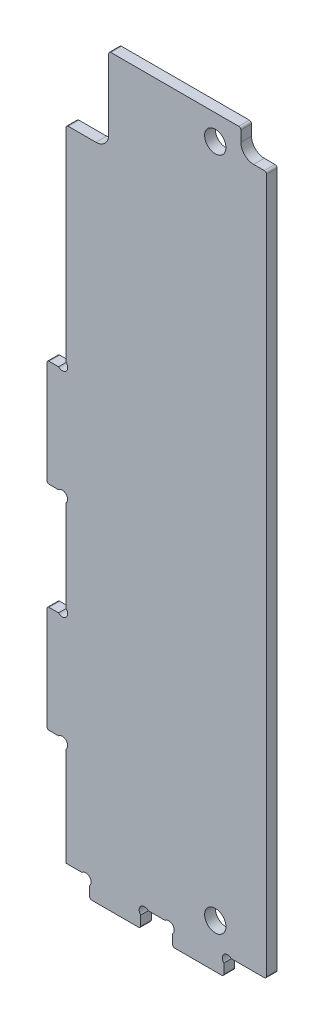
SolidWorks part; units mm, degrees
ref_plane "Ebene vorne" through (0, 0, 0) normal (0, 0, 1) x (1, 0, 0)
ref_plane "Ebene oben" through (0, 0, 0) normal (0, 1, 0) x (1, 0, 0)
ref_plane "Ebene rechts" through (0, 0, 0) normal (1, 0, 0) x (0, 0, -1)
sketch "Sketch1" plane through (0, 0, 0) normal (0, 0, 1) x (1, 0, 0)
  line L1 (0, 0) -> (5.5, 0)
  line L2 (0, 0) -> (0, 25)
  line L3 (10, 170) -> (47, 170)
  line L4 (47, 0) -> (47, 170)
  line L7 (0, 25) -> (-4.5, 25)
  line L8 (-4.5, 25) -> (-4.5, 50)
  line L9 (-4.5, 50) -> (0, 50)
  line L10 (0, 50) -> (0, 75)
  line L11 (0, 75) -> (-4.5, 75)
  line L12 (-4.5, 75) -> (-4.5, 100)
  line L13 (-4.5, 100) -> (0, 100)
  line L14 (0, 100) -> (0, 150)
  line L15 (37, 0) -> (37, -4.5)
  line L16 (0, 150) -> (10, 150)
  line L17 (10, 170) -> (10, 150)
  line L18 (37, -4.5) -> (25, -4.5)
  line L19 (25, -4.5) -> (25, 0)
  line L20 (47, 160) -> (47, -4.5) construction
  line L21 (17.5, 0) -> (17.5, -4.5)
  line L22 (17.5, -4.5) -> (5.5, -4.5)
  line L23 (5.5, -4.5) -> (5.5, 0)
  line L24 (37, 0) -> (47, 0)
  line L25 (17.5, 0) -> (25, 0)
  circle A0 centre (35, 5.85) radius 2.5
  circle A1 centre (35, 164.15) radius 2.5
  dimension "D3" = 5
  dimension "D2" = 170
  dimension "D4" = 12
  dimension "D5" = 5.85
  dimension "D6" = 25
  dimension "D7" = 4.5
  dimension "D8" = 25
  dimension "D9" = 47
  dimension "D10" = 5.85
  dimension "D11" = 12
  dimension "D12" = 4.5
  dimension "D13" = 10
  dimension "D14" = 10
  dimension "D15" = 7.5
  dimension "D16" = 12
  dimension "D17" = 20
extrude "Boss-Extrude1" add sketch "Sketch1" along normal blind 2.5
sketch "Sketch3" plane through (0, 0, 2.5) normal (0, 0, 1) x (1, 0, 0)
  line L0 (47, 170) -> (10, 170) construction
  line L2 (41, 170) -> (47, 170)
  line L3 (41, 170) -> (41, 164)
  line L4 (41, 164) -> (47, 164)
  line L5 (47, 170) -> (47, 164)
  line L6 (47, 0) -> (47, 170) construction
  dimension "D1" = 6
  dimension "D2" = 6
extrude "Cut-Extrude2" cut sketch "Sketch3" against normal through all
sketch "Sketch2" plane through (0, 0, 2.5) normal (0, 0, 1) x (1, 0, 0)
  line L0 (-0.8839, 24.1161) -> (-0.8839, 25) construction
  line L1 (0, 25) -> (0, 0) construction
  line L3 (-0.8839, 24.1161) -> (0, 24.1161) construction
  line L4 (-4.5, 25) -> (0, 25) construction
  line L8 (-4.5, 50) -> (-4.5, 25) construction
  line L9 (-4.5, 37.5) -> (-10.3856, 37.5) construction
  line L11 (0, 75) -> (0, 50) construction
  line L12 (0, 62.5) -> (-7.4428, 62.5) construction
  line L14 (-4.5, 100) -> (-4.5, 75) construction
  line L15 (-4.5, 87.5) -> (-15.0134, 87.5) construction
  line L31 (5.5, -0.8839) -> (4.6161, -0.8839) construction
  line L33 (5.5, 0) -> (5.5, -4.5) construction
  line L34 (4.6161, -0.8839) -> (4.6161, 0) construction
  line L36 (5.5, -4.5) -> (17.5, -4.5) construction
  line L37 (11.5, -4.5) -> (11.5, -1.3725) construction
  line L39 (17.5, 0) -> (25, 0) construction
  line L40 (21.25, 0) -> (21.25, -3.5992) construction
  line L41 (0, 0) -> (5.5, 0) construction
  line L42 (25, -4.5) -> (37, -4.5) construction
  line L43 (31, -4.5) -> (31, -0.6862) construction
  circle A0 centre (-0.8839, 24.1161) radius 1.25
  circle A1 centre (-0.8839, 50.8839) radius 1.25
  circle A2 centre (-0.8839, 74.1161) radius 1.25
  circle A3 centre (-0.8839, 100.8839) radius 1.25
  circle A12 centre (4.6161, -0.8839) radius 1.25
  circle A13 centre (18.3839, -0.8839) radius 1.25
  circle A14 centre (24.1161, -0.8839) radius 1.25
  circle A15 centre (37.8839, -0.8839) radius 1.25
  dimension "D1" = 2.5
  dimension "D2" = 2.5
extrude "Cut-Extrude1" cut sketch "Sketch2" against normal through all
fillet "Fillet1" radius 0.5 13 edges at (-4.5, 75, 1.25) (-4.5, 100, 1.25) (-4.5, 25, 1.25) (-4.5, 50, 1.25) (5.5, -4.5, 1.25) (17.5, -4.5, 1.25) (25, -4.5, 1.25) (37, -4.5, 1.25) (47, 0, 1.25) (47, 164, 1.25) (41, 170, 1.25) (10, 170, 1.25) (0, 150, 1.25)
fillet "Fillet2" radius 3 2 edges at (41, 164, 1.25) (10, 150, 1.25)
